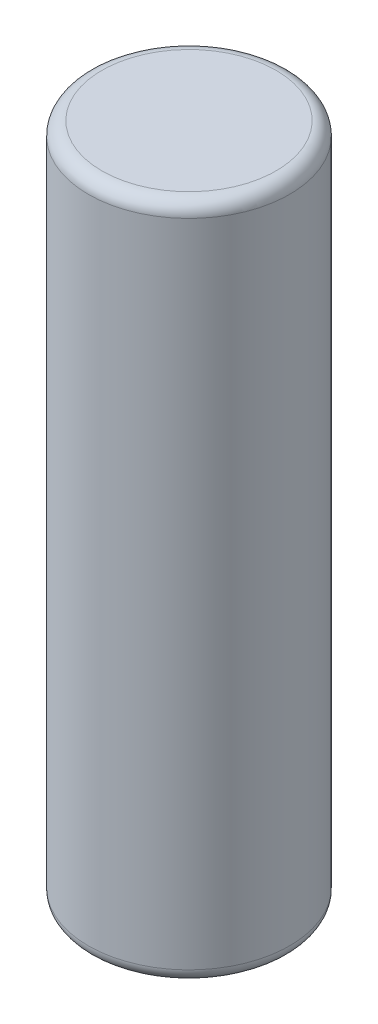
SolidWorks part; units mm, degrees
ref_plane "Alzado" through (0, 0, 0) normal (0, 0, 1) x (1, 0, 0)
ref_plane "Planta" through (0, 0, 0) normal (0, 1, 0) x (1, 0, 0)
ref_plane "Vista lateral" through (0, 0, 0) normal (1, 0, 0) x (0, 0, -1)
sketch "Croquis1" plane through (0, 0, 0) normal (0, 1, 0) x (1, 0, 0)
  circle A0 centre (0, 0) radius 7.425
  dimension "D1" = 14.85
extrude "Saliente-Extruir1" add sketch "Croquis1" along normal blind 50
fillet "Redondeo1" radius 1 2 edges at (0, 0, 7.425) (0, 50, 7.425)
